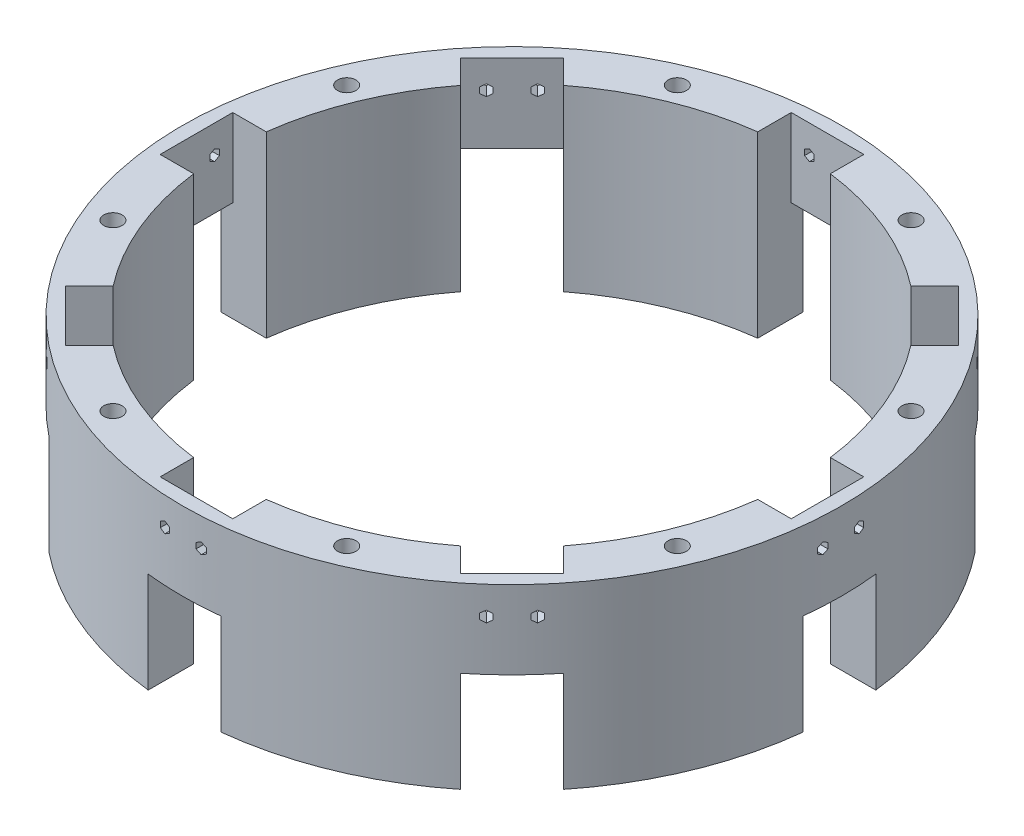
SolidWorks part; units mm, degrees
material "ABS"
ref_plane "Front Plane" through (0, 0, 0) normal (0, 0, 1) x (1, 0, 0)
ref_plane "Top Plane" through (0, 0, 0) normal (0, 1, 0) x (1, 0, 0)
ref_plane "Right Plane" through (0, 0, 0) normal (1, 0, 0) x (0, 0, -1)
sketch "Sketch1" plane through (0, 0, 0) normal (0, 1, 0) x (1, 0, 0)
  circle A0 centre (0, 0) radius 50.5
  circle A1 centre (0, 0) radius 62.5
  dimension "D1" = 101
  dimension "D2" = 125
extrude "Boss-Extrude1" add sketch "Sketch1" along normal blind 32
sketch "Sketch2" plane through (0, 32, 0) normal (0, 1, 0) x (1, 0, 0)
  line L173 (35.3553, 44.5477) -> (31.1127, 40.3051)
  line L241 (-6.5, 56.5) -> (6.5, 56.5)
  line L242 (-6.5, 56.5) -> (-6.5, 50.5)
  line L244 (6.5, 56.5) -> (6.5, 50.5)
  line L245 (35.3553, 44.5477) -> (44.5477, 35.3553)
  line L246 (44.5477, 35.3553) -> (40.3051, 31.1127)
  line L248 (56.5, 6.5) -> (50.5, 6.5)
  line L249 (56.5, 6.5) -> (56.5, -6.5)
  line L250 (56.5, -6.5) -> (50.5, -6.5)
  line L252 (44.5477, -35.3553) -> (40.3051, -31.1127)
  line L253 (44.5477, -35.3553) -> (35.3553, -44.5477)
  line L254 (35.3553, -44.5477) -> (31.1127, -40.3051)
  line L256 (6.5, -56.5) -> (6.5, -50.5)
  line L257 (6.5, -56.5) -> (-6.5, -56.5)
  line L258 (-6.5, -56.5) -> (-6.5, -50.5)
  line L260 (-35.3553, -44.5477) -> (-31.1127, -40.3051)
  line L261 (-35.3553, -44.5477) -> (-44.5477, -35.3553)
  line L262 (-44.5477, -35.3553) -> (-40.3051, -31.1127)
  line L264 (-56.5, -6.5) -> (-50.5, -6.5)
  line L265 (-56.5, -6.5) -> (-56.5, 6.5)
  line L266 (-56.5, 6.5) -> (-50.5, 6.5)
  line L268 (-44.5477, 35.3553) -> (-40.3051, 31.1127)
  line L269 (-44.5477, 35.3553) -> (-35.3553, 44.5477)
  line L270 (-35.3553, 44.5477) -> (-31.1127, 40.3051)
  arc A67 (-6.5, 50.5) -> (-31.1127, 40.3051) centre (0, 0) ccw
  arc A68 (31.1127, 40.3051) -> (6.5, 50.5) centre (0, 0) ccw
  arc A69 (50.5, 6.5) -> (40.3051, 31.1127) centre (0, 0) ccw
  arc A70 (40.3051, -31.1127) -> (50.5, -6.5) centre (0, 0) ccw
  arc A71 (6.5, -50.5) -> (31.1127, -40.3051) centre (0, 0) ccw
  arc A72 (-31.1127, -40.3051) -> (-6.5, -50.5) centre (0, 0) ccw
  arc A73 (-50.5, -6.5) -> (-40.3051, -31.1127) centre (0, 0) ccw
  arc A74 (-40.3051, 31.1127) -> (-50.5, 6.5) centre (0, 0) ccw
  point P40 (0, 0)
  dimension "D1" = 6
  dimension "D2" = 13
  dimension "D4" = 56.8727
  dimension "D5" = 31.2328
  dimension "D3" = 8
extrude "Cut-Extrude3" cut sketch "Sketch2" against normal through all contours L242 A67 L270 L269 L268 A74 L266 L265 L264 A73 L262 L261 L260 A72 L258 L257 L256 A71 L254 L253 L252 A70 L250 L249 L248 A69 L246 L245 L173 A68 L244 L241
sketch "Sketch7" plane through (0, 0, 0) normal (0, -1, 0) x (1, 0, 0)
  line L0 (-56.5, 6.5) -> (-44.5477, 35.3553) construction
  circle A1 centre (-20.9277, 50.5239) radius 1.65
  circle A53 centre (-50.5239, 20.9277) radius 1.65
  circle A55 centre (20.9277, 50.5239) radius 1.65
  circle A56 centre (50.5239, 20.9277) radius 1.65
  circle A57 centre (50.5239, -20.9277) radius 1.65
  circle A58 centre (20.9277, -50.5239) radius 1.65
  circle A59 centre (-20.9277, -50.5239) radius 1.65
  circle A60 centre (-50.5239, -20.9277) radius 1.65
  point P23 (0, 0)
  dimension "D1" = 3.3
  dimension "D4" = 50.5239
  dimension "D3" = 41.8553
  dimension "D2" = 8
extrude "Cut-Extrude5" cut sketch "Sketch7" against normal through all
sketch "Sketch9" plane through (39.9515, 0, -39.9515) normal (-0.7071, 0, 0.7071) x (0.7071, 0, 0.7071)
  line L0 (-3.25, 27) -> (3.25, 27) construction
  line L1 (0, 0) -> (0, 27) construction
  line L2 (-6.5, 0) -> (6.5, 0) construction
  line L3 (-6.5, 32) -> (6.5, 32) construction
  line L4 (-3.25, 28) -> (-4.116, 27.5)
  line L5 (-4.116, 27.5) -> (-4.116, 26.5)
  line L6 (-4.116, 26.5) -> (-3.25, 26)
  line L7 (-3.25, 26) -> (-2.384, 26.5)
  line L8 (-2.384, 26.5) -> (-2.384, 27.5)
  line L9 (-2.384, 27.5) -> (-3.25, 28)
  line L10 (3.25, 28) -> (2.384, 27.5)
  line L11 (2.384, 27.5) -> (2.384, 26.5)
  line L12 (2.384, 26.5) -> (3.25, 26)
  line L13 (3.25, 26) -> (4.116, 26.5)
  line L14 (4.116, 26.5) -> (4.116, 27.5)
  line L15 (4.116, 27.5) -> (3.25, 28)
  line L16 (6.5, 0) -> (6.5, 32) construction
  line L17 (-6.5, 0) -> (6.5, 0)
  line L18 (-6.5, 0) -> (-6.5, 18)
  line L19 (-6.5, 18) -> (6.5, 18)
  line L20 (6.5, 0) -> (6.5, 18)
  circle A0 centre (-3.25, 27) radius 0.866 construction
  circle A1 centre (3.25, 27) radius 0.866 construction
  dimension "D1" = 6.5
  dimension "D2" = 2
  dimension "D3" = 5
  dimension "D4" = 18
extrude "Cut-Extrude6" cut sketch "Sketch9" against normal through all
pattern_circular "CirPattern1" count 8 over 360 about axis through (0, 0, 0) along (0, 1, 0) of "Cut-Extrude6"
sketch "Sketch10" plane through (0, 32, 0) normal (0, 1, 0) x (1, 0, 0)
  circle A0 centre (0, 0) radius 59
  circle A1 centre (0, 0) radius 62.5
  circle A2 centre (0, 0) radius 62.5 construction
  dimension "D1" = 118
extrude "Cut-Extrude7" cut sketch "Sketch10" against normal through all
